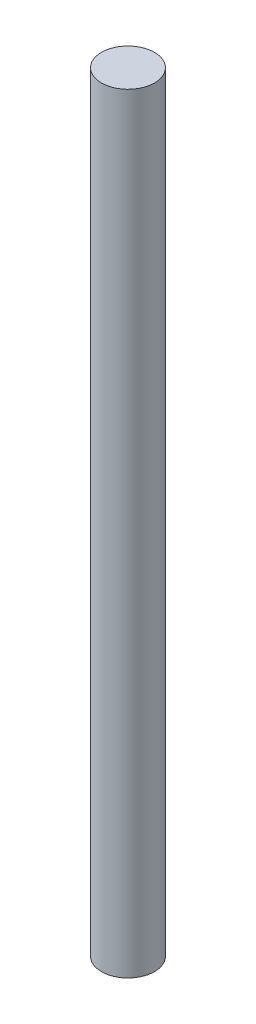
SolidWorks part; units mm, degrees
ref_plane "Front Plane" through (0, 0, 0) normal (0, 0, 1) x (1, 0, 0)
ref_plane "Top Plane" through (0, 0, 0) normal (0, 1, 0) x (1, 0, 0)
ref_plane "Right Plane" through (0, 0, 0) normal (1, 0, 0) x (0, 0, -1)
sketch "Sketch1" plane through (0, 0, 0) normal (0, 1, 0) x (1, 0, 0)
  circle A0 centre (0, 0) radius 1.75
  dimension "D1" = 3.5
extrude "Boss-Extrude1" add sketch "Sketch1" along normal blind 50.8
